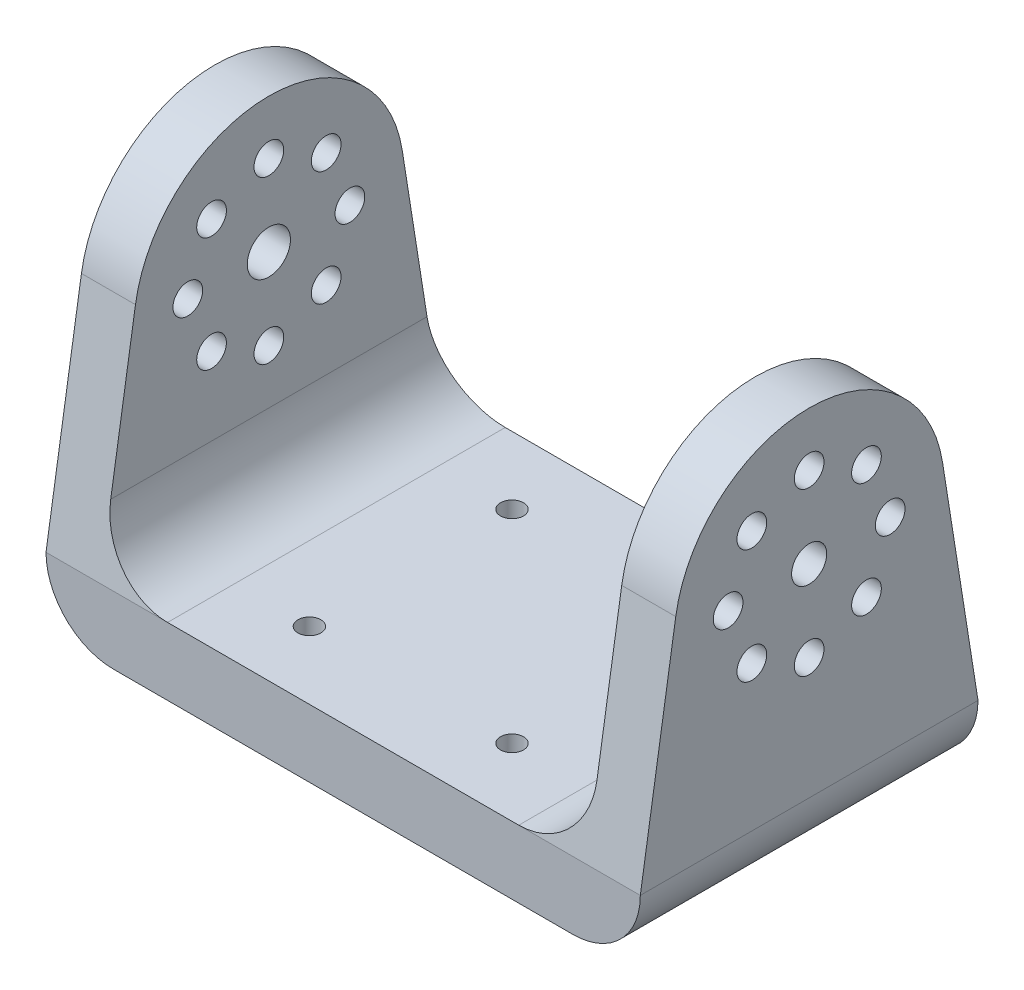
SolidWorks part; units mm, degrees
material "ABS"
ref_plane "正面" through (0, 0, 0) normal (0, 0, 1) x (1, 0, 0)
ref_plane "平面" through (0, 0, 0) normal (0, 1, 0) x (1, 0, 0)
ref_plane "右側面" through (0, 0, 0) normal (1, 0, 0) x (0, 0, -1)
sketch "ｽｹｯﾁ1" plane through (0, 0, 0) normal (0, 1, 0) x (1, 0, 0)
  line L1 (22, 0) -> (-22, 0)
  line L2 (22, 0) -> (22, 25)
  line L3 (22, 25) -> (-22, 25)
  line L4 (-22, 0) -> (-22, 25)
  dimension "D1" = 44
  dimension "D2" = 25
extrude "ﾎﾞｽ - 押し出し1" add sketch "ｽｹｯﾁ1" along normal blind 5
sketch "ｽｹｯﾁ2" plane through (-22, 0, 0) normal (-1, 0, 0) x (0, 0, 1)
  line L0 (-25, 5) -> (0, 5)
  line L1 (0, 5) -> (-2.6231, 21.5641)
  line L2 (-22.3769, 21.5641) -> (-25, 5)
  line L3 (-12.5, 5) -> (-12.5, 20) construction
  arc A0 (-2.6231, 21.5641) -> (-22.3769, 21.5641) centre (-12.5, 20) ccw
  circle A1 centre (-12.5, 20) radius 6 construction
  circle A2 centre (-12.5, 26) radius 1.1
  circle A3 centre (-8.2574, 24.2426) radius 1.1
  circle A4 centre (-6.5, 20) radius 1.1
  circle A5 centre (-8.2574, 15.7574) radius 1.1
  circle A6 centre (-12.5, 14) radius 1.1
  circle A7 centre (-16.7426, 15.7574) radius 1.1
  circle A8 centre (-18.5, 20) radius 1.1
  circle A9 centre (-16.7426, 24.2426) radius 1.1
  circle A10 centre (-12.5, 20) radius 1.6
  point P28 (-12.5, 20)
  dimension "D1" = 20
  dimension "D3" = 12
  dimension "D4" = 2.2
  dimension "D6" = 3.2
  dimension "D2" = 15
  dimension "D5" = 8
extrude "ﾎﾞｽ - 押し出し2" add sketch "ｽｹｯﾁ2" against normal blind 4
sketch "ｽｹｯﾁ3" plane through (22, 0, 0) normal (1, 0, 0) x (0, 0, -1)
  line L2 (25, 5) -> (0, 5) construction
  line L3 (0, 5) -> (2.6231, 21.5641)
  line L4 (22.3769, 21.5641) -> (25, 5)
  line L5 (25, 5) -> (0, 5)
  arc A1 (22.3769, 21.5641) -> (2.6231, 21.5641) centre (12.5, 20) ccw
  circle A2 centre (12.5, 20) radius 1.3
  circle A3 centre (12.5, 20) radius 1.6 construction
  arc A4 (22.3769, 21.5641) -> (2.6231, 21.5641) centre (12.5, 20) ccw construction
  circle A6 centre (8.2574, 15.7574) radius 1.1 construction
  circle A7 centre (12.5, 14) radius 1.1 construction
  circle A8 centre (16.7426, 15.7574) radius 1.1 construction
  circle A9 centre (18.5, 20) radius 1.1 construction
  circle A10 centre (16.7426, 24.2426) radius 1.1 construction
  circle A11 centre (12.5, 26) radius 1.1 construction
  circle A12 centre (8.2574, 24.2426) radius 1.1 construction
  circle A13 centre (6.5, 20) radius 1.1 construction
  circle A14 centre (8.2574, 15.7574) radius 1.1
  circle A15 centre (12.5, 14) radius 1.1
  circle A16 centre (16.7426, 15.7574) radius 1.1
  circle A17 centre (18.5, 20) radius 1.1
  circle A18 centre (16.7426, 24.2426) radius 1.1
  circle A19 centre (12.5, 26) radius 1.1
  circle A20 centre (8.2574, 24.2426) radius 1.1
  circle A21 centre (6.5, 20) radius 1.1
  dimension "D1" = 2.6
extrude "ﾎﾞｽ - 押し出し3" add sketch "ｽｹｯﾁ3" against normal blind 4
fillet "ﾌｨﾚｯﾄ1" radius 5 4 edges at (18, 5, -12.5) (-18, 5, -12.5) (22, 0, -12.5) (-22, 0, -12.5)
sketch "ｽｹｯﾁ4" plane through (0, 5, 0) normal (0, 1, 0) x (1, 0, 0)
  line L0 (0, 25) -> (0, 0) construction
  line L1 (13, 25) -> (-13, 25) construction
  line L2 (-13, 0) -> (13, 0) construction
  line L3 (-13, 12.5) -> (13, 12.5) construction
  line L4 (-13, 25) -> (-13, 0) construction
  line L5 (13, 0) -> (13, 25) construction
  line L7 (-7.5, 20) -> (7.5, 20) construction
  line L8 (-7.5, 20) -> (-7.5, 5) construction
  line L9 (-7.5, 5) -> (7.5, 5) construction
  line L10 (7.5, 20) -> (7.5, 5) construction
  line L11 (-7.5, 20) -> (7.5, 5) construction
  line L12 (-7.5, 5) -> (7.5, 20) construction
  circle A0 centre (-7.5, 20) radius 0.85
  circle A1 centre (7.5, 20) radius 0.85
  circle A2 centre (7.5, 5) radius 0.85
  circle A3 centre (-7.5, 5) radius 0.85
  point P12 (0, 12.5)
  dimension "D3" = 1.7
  dimension "D1" = 15
  dimension "D2" = 15
extrude "ｶｯﾄ - 押し出し1" cut sketch "ｽｹｯﾁ4" against normal blind 5
